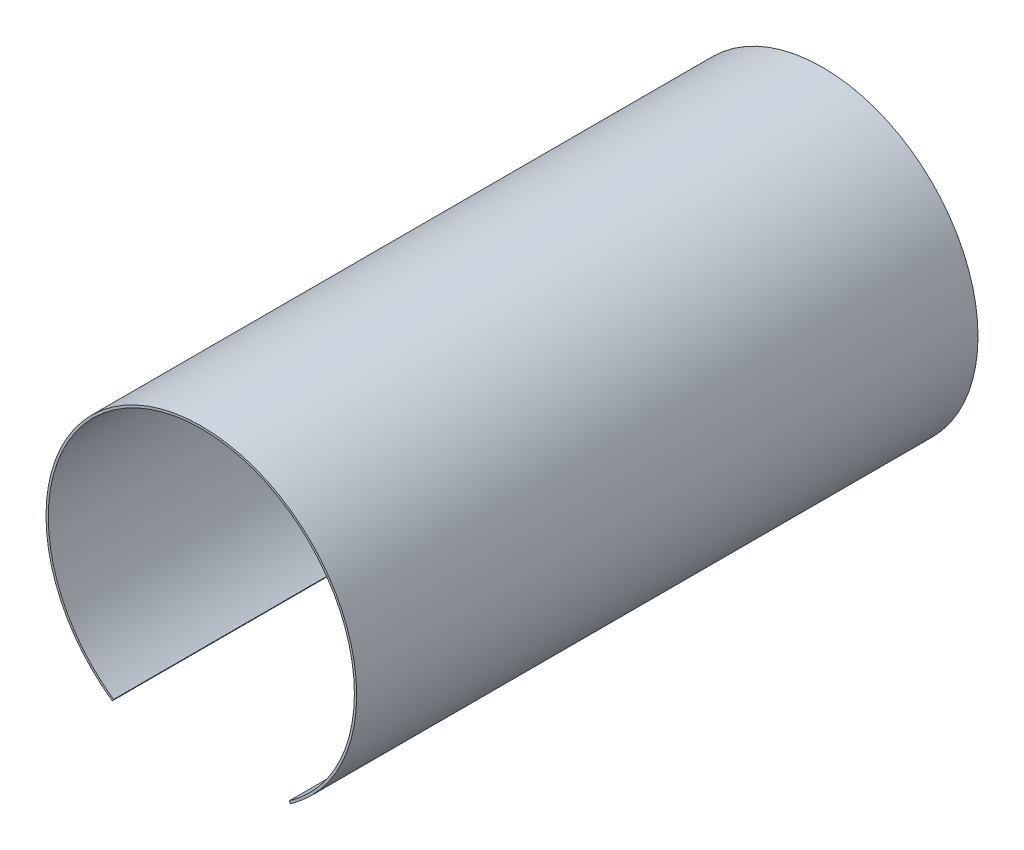
SolidWorks part; units mm, degrees
ref_plane "Front" through (0, 0, 0) normal (0, 0, 1) x (1, 0, 0)
ref_plane "Top" through (0, 0, 0) normal (0, 1, 0) x (1, 0, 0)
ref_plane "Right" through (0, 0, 0) normal (1, 0, 0) x (0, 0, -1)
sketch "Esquisse1" plane through (0, 0, 0) normal (0, 0, 1) x (1, 0, 0)
  line L0 (0, 101) -> (0, 0) construction
  line L1 (-57.9312, -82.7344) -> (0, 0) construction
  line L2 (-58.7916, -83.9631) -> (-57.9312, -82.7344)
  line L3 (57.9312, -82.7344) -> (58.7916, -83.9631)
  arc A0 (-57.9312, -82.7344) -> (57.9312, -82.7344) centre (0, 0) cw
  arc A1 (-58.7916, -83.9631) -> (58.7916, -83.9631) centre (0, 0) cw
  dimension "D2" = 101
  dimension "D1" = 145
  dimension "D3" = 1.5
extrude "Boss.-Extru.1" add sketch "Esquisse1" along normal blind 410
